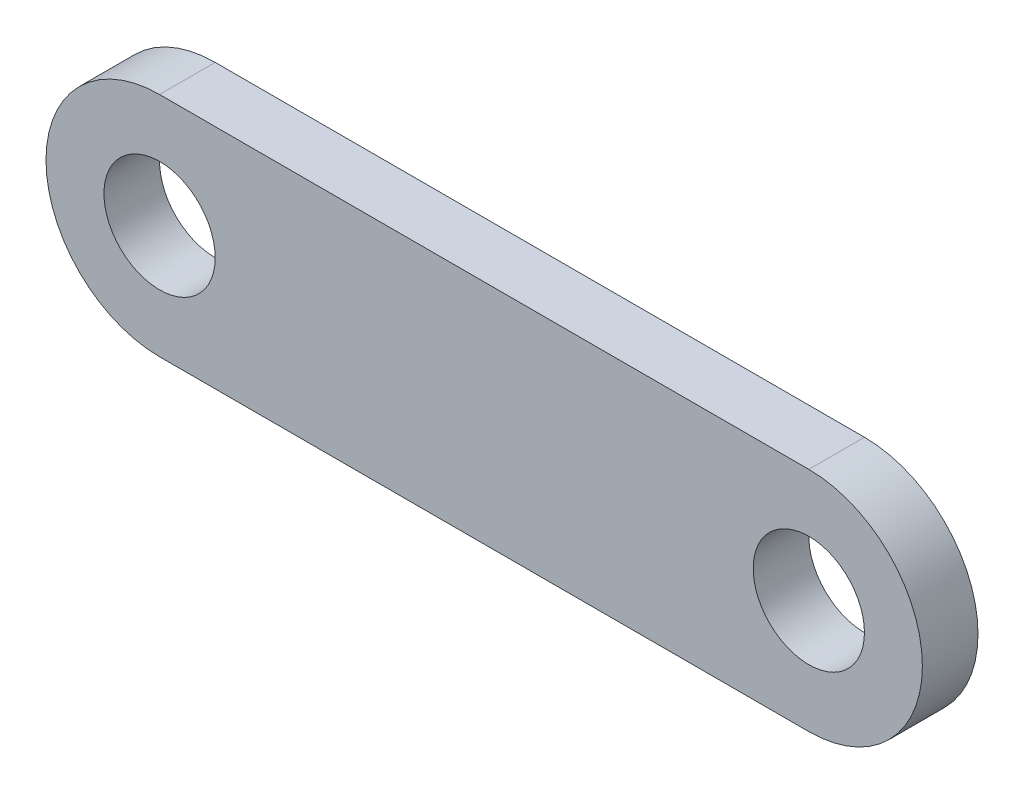
SolidWorks part; units mm, degrees
ref_plane "Plano frontal" through (0, 0, 0) normal (0, 0, 1) x (1, 0, 0)
ref_plane "Plano superior" through (0, 0, 0) normal (0, 1, 0) x (1, 0, 0)
ref_plane "Plano direito" through (0, 0, 0) normal (1, 0, 0) x (0, 0, -1)
sketch "Esboço1" plane through (0, 0, 0) normal (0, 0, 1) x (1, 0, 0)
  line L0 (-5.835, 2.0413) -> (5.835, 2.0413)
  line L1 (-5.835, 0) -> (5.835, 0) construction
  line L2 (-5.835, -2.0413) -> (5.835, -2.0413)
  arc A0 (-5.835, 2.0413) -> (-5.835, -2.0413) centre (-5.835, 0) ccw
  arc A1 (5.835, 2.0413) -> (5.835, -2.0413) centre (5.835, 0) cw
  circle A2 centre (-5.835, 0) radius 1
  circle A3 centre (5.835, 0) radius 1
  point P3 (0, 2.0413)
  dimension "D1" = 11.67
extrude "Ressalto-extrusão1" add sketch "Esboço1" along normal blind 1
